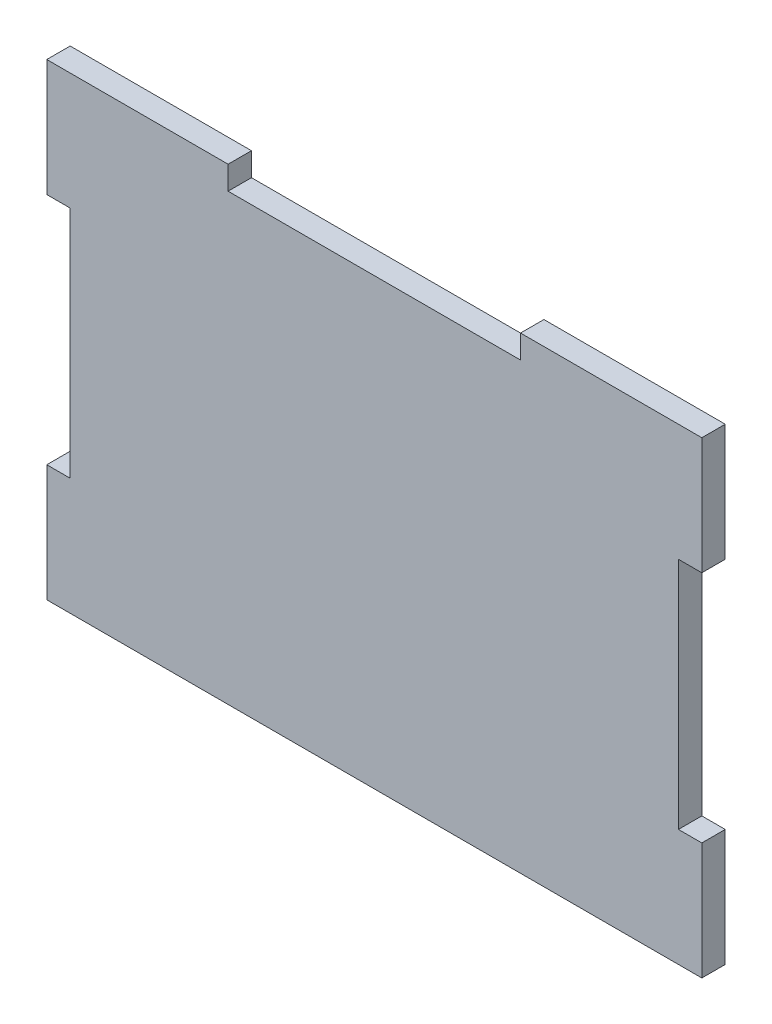
SolidWorks part; units mm, degrees
ref_plane "정면" through (0, 0, 0) normal (0, 0, 1) x (1, 0, 0)
ref_plane "윗면" through (0, 0, 0) normal (0, 1, 0) x (1, 0, 0)
ref_plane "우측면" through (0, 0, 0) normal (1, 0, 0) x (0, 0, -1)
sketch "스케치1" plane through (0, 0, 0) normal (0, 0, 1) x (1, 0, 0)
  line L1 (-4, 40) -> (108, 40)
  line L2 (-4, 40) -> (-4, -40)
  line L3 (-4, -40) -> (108, -40)
  line L4 (108, 40) -> (108, -40)
extrude "보스-돌출1" add sketch "스케치1" along normal blind 4
sketch "스케치2" plane through (0, 0, 4) normal (0, 0, 1) x (1, 0, 0)
  line L0 (0, -20) -> (-4, -20) construction
  line L1 (-4, 40) -> (27, 40)
  line L2 (-4, 40) -> (-4, 20)
  line L3 (-4, -40) -> (108, -40)
  line L4 (108, 40) -> (108, 20)
  line L5 (0, 20) -> (-4, 20)
  line L6 (0, 20) -> (0, -20)
  line L7 (0, -20) -> (-4, -20)
  line L9 (77, 36) -> (77, 40) construction
  line L10 (27, 36) -> (77, 36)
  line L11 (27, 36) -> (27, 40)
  line L13 (77, 36) -> (77, 40)
  line L14 (108, -20) -> (104, -20) construction
  line L15 (104, 20) -> (108, 20)
  line L16 (104, 20) -> (104, -20)
  line L17 (104, -20) -> (108, -20)
  line L19 (77, 40) -> (108, 40)
  line L20 (-4, -20) -> (-4, -40)
  line L21 (108, -20) -> (108, -40)
  line M1 (-4, 40) -> (-4, -40)
  line M3 (108, -40) -> (108, 40)
  line M4 (108, 40) -> (-4, 40)
extrude "컷-돌출1" cut sketch "스케치2" against normal blind 4 contours L7 L6 L5 M1 | L10 L13 L11 M4 | L16 L17 L15 M3
